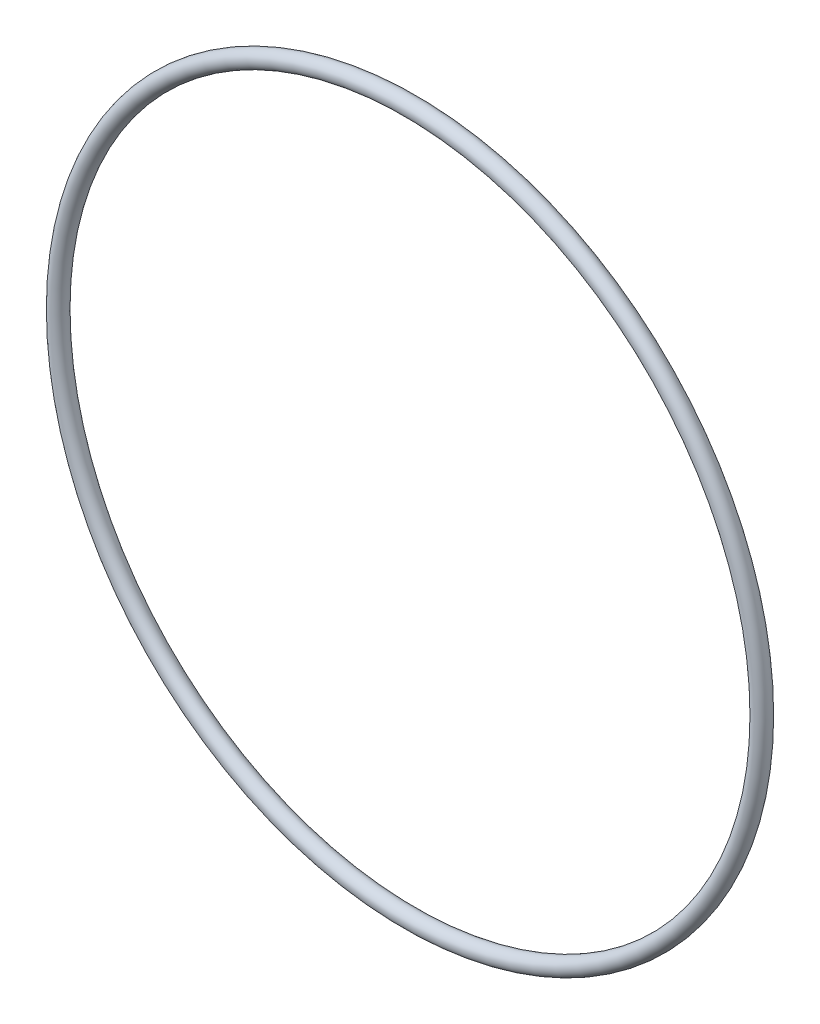
SolidWorks part; units mm, degrees
ref_plane "Front Plane" through (0, 0, 0) normal (0, 0, 1) x (1, 0, 0)
ref_plane "Top Plane" through (0, 0, 0) normal (0, 1, 0) x (1, 0, 0)
ref_plane "Right Plane" through (0, 0, 0) normal (1, 0, 0) x (0, 0, -1)
sketch "Sketch1" plane through (0, 0, 0) normal (1, 0, 0) x (0, 0, -1)
  line L0 (-2.5354, 0) -> (2.5354, 0) construction
  circle A0 centre (0, 52.5) radius 1.25
  point P6 (0, 0)
  dimension "D1" = 2.5
  dimension "D2" = 52.5
revolve "Revolve1" add sketch "Sketch1" angle 360 about L0
